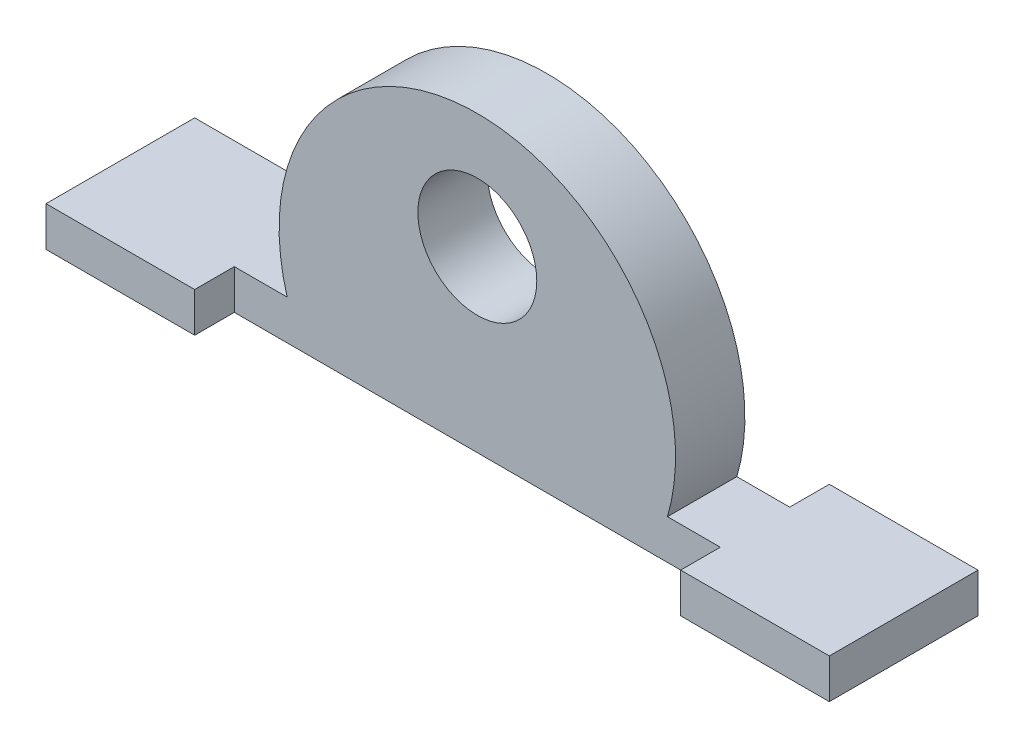
SolidWorks part; units mm, degrees
ref_plane "Front Plane" through (0, 0, 0) normal (0, 0, 1) x (1, 0, 0)
ref_plane "Top Plane" through (0, 0, 0) normal (0, 1, 0) x (1, 0, 0)
ref_plane "Right Plane" through (0, 0, 0) normal (1, 0, 0) x (0, 0, -1)
sketch "Sketch1" plane through (0, 0, 0) normal (0, 0, 1) x (1, 0, 0)
  line L4 (17.5178, -9.6501) -> (-17.5178, -9.6501)
  arc A2 (17.5178, -9.6501) -> (-17.5178, -9.6501) centre (0, 0) ccw
  circle A3 centre (0, 8.3499) radius 6
extrude "Boss-Extrude1" add sketch "Sketch1" along normal blind 7
sketch "Sketch4" plane through (0, 0, 7) normal (0, 0, 1) x (1, 0, 0)
  line L0 (0, 0) -> (0, 29.6037)
ref_plane "Plane1" through (0, 0, 0) normal (1, 0, 0) x (0, 1, 0)
sketch "Sketch5" plane through (0, -9.6501, 0) normal (0, -1, 0) x (1, 0, 0)
  line L0 (-24.5178, -4) -> (-24.5178, 0)
  line L1 (-17.5178, 7) -> (-24.5178, 7)
  line L2 (-17.5178, 7) -> (-17.5178, 0)
  line L3 (-17.5178, 0) -> (-24.5178, 0)
  line L13 (-24.5178, 11) -> (-39.5178, 11)
  line L14 (-39.5178, 11) -> (-39.5178, -4)
  line L15 (-24.5178, -4) -> (-39.5178, -4)
  line L16 (-24.5178, 7) -> (-24.5178, 11)
  line L18 (24.5178, -4) -> (39.5178, -4)
  line L19 (39.5178, 11) -> (39.5178, -4)
  line L20 (24.5178, 11) -> (39.5178, 11)
  line L22 (17.5178, 0) -> (24.5178, 0)
  line L23 (17.5178, 7) -> (17.5178, 0)
  line L24 (17.5178, 7) -> (24.5178, 7)
  line L25 (24.5178, -4) -> (24.5178, 0)
  line L26 (24.5178, 7) -> (24.5178, 11)
extrude "Boss-Extrude2" add sketch "Sketch5" against normal blind 4
